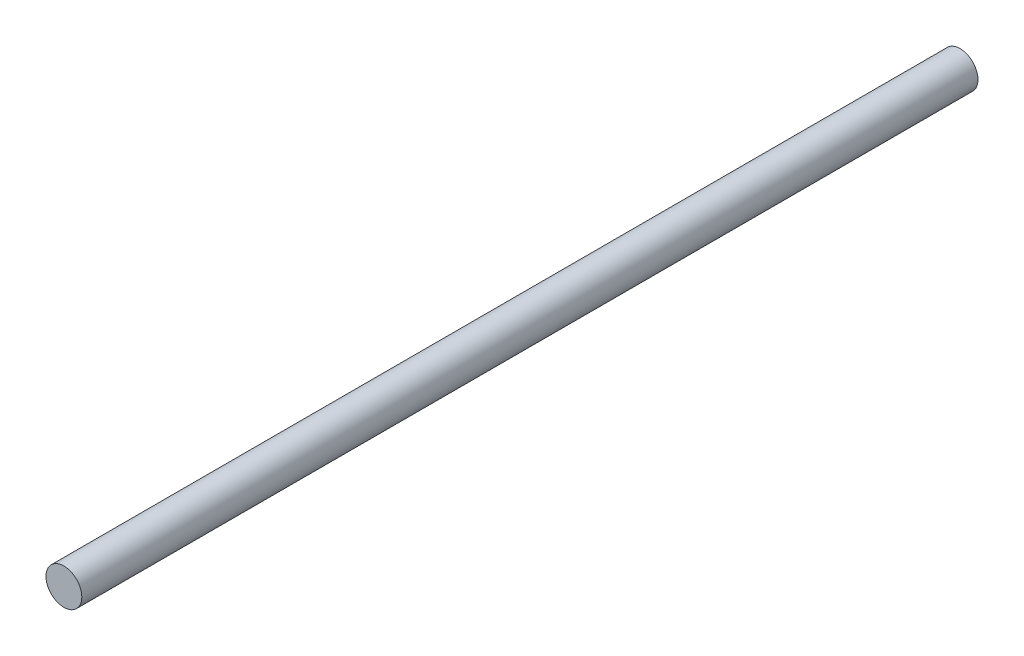
SolidWorks part; units mm, degrees
ref_plane "Front Plane" through (0, 0, 0) normal (0, 0, 1) x (1, 0, 0)
ref_plane "Top Plane" through (0, 0, 0) normal (0, 1, 0) x (1, 0, 0)
ref_plane "Right Plane" through (0, 0, 0) normal (1, 0, 0) x (0, 0, -1)
sketch "Sketch1" plane through (0, 0, 0) normal (0, 0, 1) x (1, 0, 0)
  circle A0 centre (0, 0) radius 20
  point P3 (-549.2884, 251.814)
  dimension "D1" = 40
extrude "Boss-Extrude1" add sketch "Sketch1" along normal blind 1000
ref_plane "Plane1" through (0, 0, 50) normal (0, 0, -1) x (-1, 0, 0)
sketch "Sketch3" plane through (0, 0, 0) normal (0, 0, -1) x (-1, 0, 0)
  line L0 (-19.9869, 0.723) -> (19.9869, -0.723) construction
  circle A0 centre (0, 0) radius 20 construction
